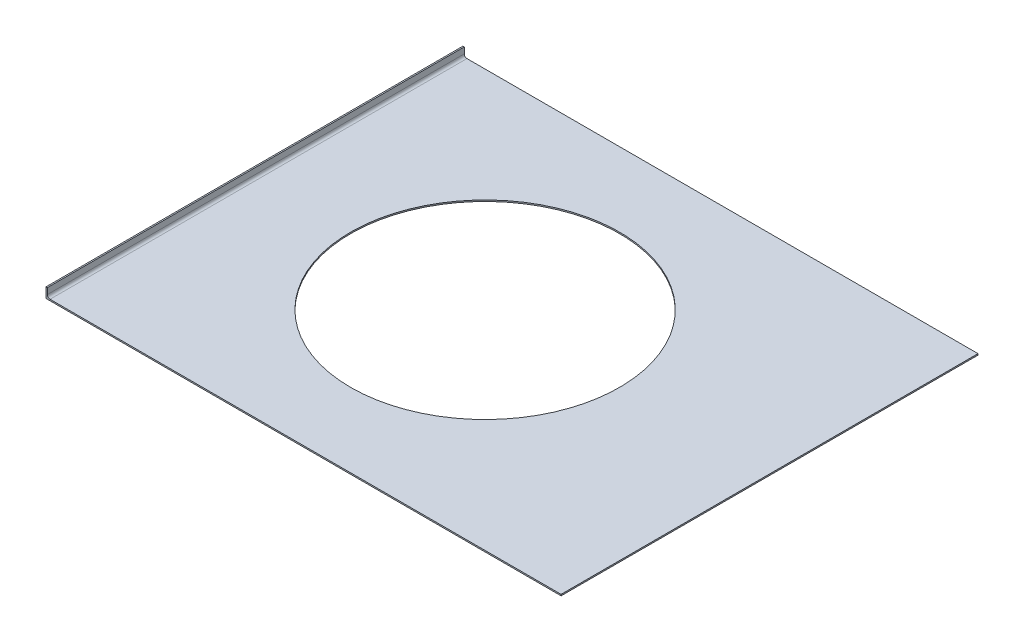
SolidWorks part; units mm, degrees
ref_plane "Front Plane" through (0, 0, 0) normal (0, 0, 1) x (1, 0, 0)
ref_plane "Top Plane" through (0, 0, 0) normal (0, 1, 0) x (1, 0, 0)
ref_plane "Right Plane" through (0, 0, 0) normal (1, 0, 0) x (0, 0, -1)
sketch "Sketch1" plane through (0, 0, 0) normal (0, 1, 0) x (1, 0, 0)
  line L1 (243.205, 196.85) -> (-243.205, 196.85)
  line L2 (243.205, 196.85) -> (243.205, -196.85)
  line L3 (243.205, -196.85) -> (-243.205, -196.85)
  line L4 (-243.205, 196.85) -> (-243.205, -196.85)
  line L5 (243.205, 196.85) -> (-243.205, -196.85) construction
  line L6 (243.205, -196.85) -> (-243.205, 196.85) construction
  point P0 (0, 0)
  dimension "D1" = 486.41
  dimension "D2" = 393.7
extrude "Boss-Extrude1" add sketch "Sketch1" along normal mid plane 1.27
sketch "Sketch2" plane through (0, 0.635, 0) normal (0, 1, 0) x (1, 0, 0)
  line L0 (-243.205, 0) -> (243.205, 0) construction
  line L1 (-243.205, 196.85) -> (-243.205, -196.85) construction
  line L2 (243.205, -196.85) -> (243.205, 196.85) construction
  circle A0 centre (-25.4, 0) radius 127
  dimension "D1" = 254
  dimension "D2" = 25.4
extrude "Cut-Extrude1" cut sketch "Sketch2" against normal through all
sketch "Sketch3" plane through (0, 0.635, 0) normal (0, 1, 0) x (1, 0, 0)
  line L0 (-25.4, 0) -> (-25.4, 190.5) construction
  line L2 (-25.908, 126.999) -> (-25.908, 139.699)
  line L3 (-24.892, 139.699) -> (-24.892, 126.999)
  line L4 (-24.892, 126.999) -> (-25.908, 126.999)
  circle A0 centre (-25.4, 0) radius 127 construction
  arc A1 (-25.908, 139.699) -> (-24.892, 139.699) centre (-25.4, 141.4029) cw
  dimension "D3" = 1.778
  dimension "D1" = 1.016
  dimension "D2" = 12.7
extrude "Cut-Extrude2" [suppressed] cut sketch "Sketch3" against normal through all
pattern_circular "CirPattern1" [suppressed] count 10 over 360
sketch "Sketch6" plane through (0, 0, 0) normal (0, 0, 1) x (1, 0, 0)
  line L1 (-243.205, -0.635) -> (-241.935, -0.635)
  line L2 (-243.205, -0.635) -> (-243.205, 8.89)
  line L3 (-243.205, 8.89) -> (-241.935, 8.89)
  line L4 (-241.935, -0.635) -> (-241.935, 8.89)
  dimension "D1" = 1.27
  dimension "D2" = 9.525
extrude "Boss-Extrude2" add sketch "Sketch6" along normal up to surface and the other way up to surface up to face at (0, 0, 196.85) other way up to face at (0, 0, -196.85)
fillet "Fillet1" radius 2.54 1 edges at (-241.935, 0.635, 0)
